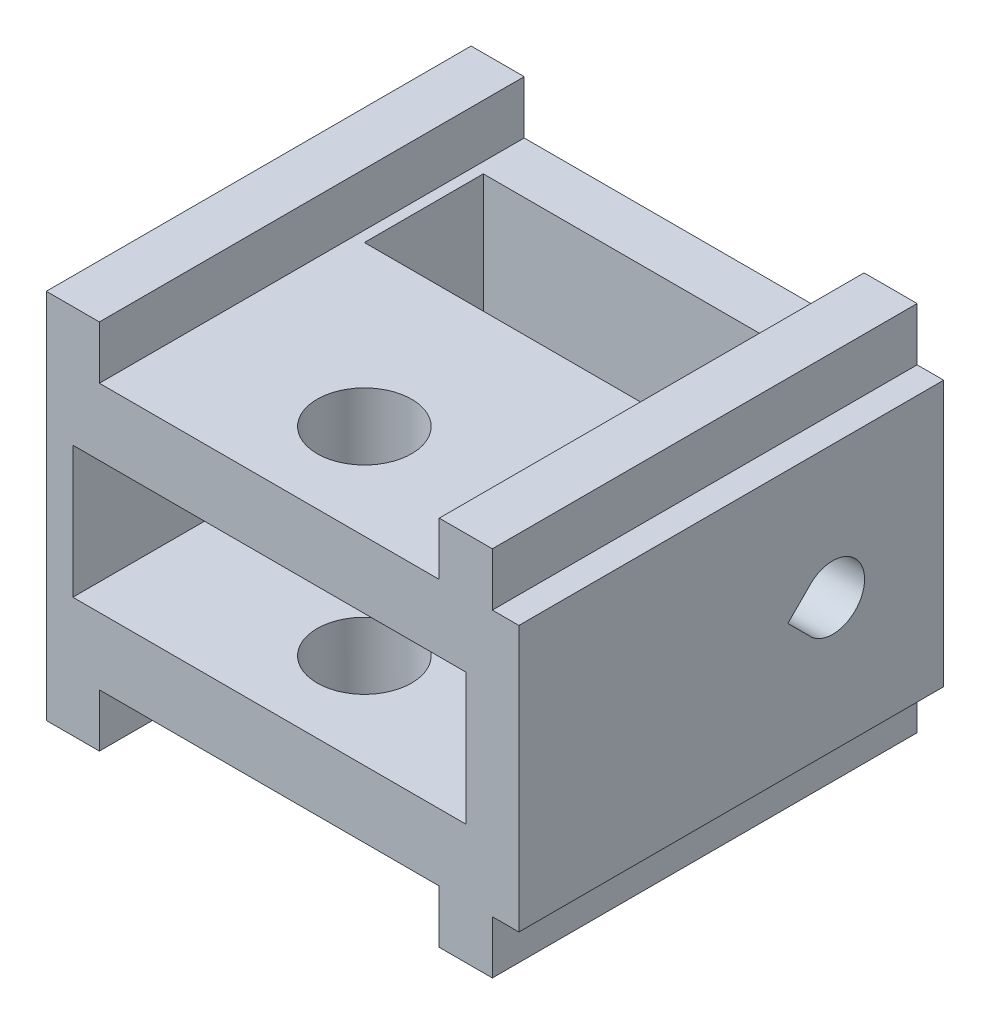
SolidWorks part; units mm, degrees
ref_plane "Front Plane" through (0, 0, 0) normal (1, 0, 0) x (0, 1, 0)
ref_plane "Top Plane" through (0, 0, 0) normal (0, 0, 1) x (0, 1, 0)
ref_plane "Right Plane" through (0, 0, 0) normal (0, 1, 0) x (-1, 0, 0)
sketch "Sketch1" plane through (0, 0, 0) normal (0, 1, 0) x (-1, 0, 0)
  line L1 (-19.5258, 0.7216) -> (22.4742, 0.7216)
  line L2 (-19.5258, 0.7216) -> (-19.5258, 40.7216)
  line L3 (-19.5258, 40.7216) -> (22.4742, 40.7216)
  line L4 (22.4742, 0.7216) -> (22.4742, 40.7216)
  dimension "D1" = 42
  dimension "D2" = 40
extrude "Boss-Extrude1" add sketch "Sketch1" along normal blind 25
sketch "Sketch2" plane through (0, 25, 0) normal (0, 1, 0) x (-1, 0, 0)
  line L0 (-19.5258, 40.7216) -> (-19.5258, 0.7216) construction
  line L1 (-13.5258, 16.7716) -> (16.4742, 16.7716)
  line L2 (-13.5258, 16.7716) -> (-13.5258, 5.5716)
  line L3 (-13.5258, 5.5716) -> (16.4742, 5.5716)
  line L4 (16.4742, 16.7716) -> (16.4742, 5.5716)
  line L5 (-19.5258, 0.7216) -> (22.4742, 0.7216) construction
  line L6 (22.4742, 0.7216) -> (22.4742, 40.7216) construction
  line L8 (-13.5258, 11.1716) -> (16.4742, 11.1716) construction
  circle A0 centre (1.4742, 31.7716) radius 4.45
  dimension "D4" = 8.9
  dimension "D5" = 15
  dimension "D6" = 21
  dimension "D7" = 11.2
  dimension "D8" = 21
  dimension "D1" = 6
  dimension "D2" = 10.45
  dimension "D3" = 30
  dimension "D9" = 31.05
  dimension "D10" = 6
extrude "Cut-Extrude1" cut sketch "Sketch2" against normal blind 25
sketch "Sketch5" plane through (0, 0, 40.7216) normal (0, 0, 1) x (1, 0, 0)
  line L1 (-19.9742, 18.7) -> (17.0258, 18.7)
  line L2 (-19.9742, 18.7) -> (-19.9742, 6.3)
  line L3 (-19.9742, 6.3) -> (17.0258, 6.3)
  line L4 (17.0258, 18.7) -> (17.0258, 6.3)
  line L8 (-22.4742, 25) -> (19.5258, 25) construction
  line L9 (-22.4742, 0) -> (19.5258, 0) construction
  line L10 (-1.4742, 25) -> (-1.4742, 0) construction
  dimension "D1" = 12.4
  dimension "D2" = 6.3
  dimension "D3" = 6.3
  dimension "D4" = 37
extrude "Cut-Extrude3" cut sketch "Sketch5" against normal up to surface (23.95 mm away) up to face at (-1.4742, 12.5, 16.7716)
sketch "Sketch7" plane through (0, 25, 0) normal (0, 1, 0) x (-1, 0, 0)
  line L0 (22.4742, 0.7216) -> (22.4742, 40.7216) construction
  line L1 (17.4742, 0.7216) -> (22.4742, 0.7216)
  line L2 (17.4742, 0.7216) -> (17.4742, 40.7216)
  line L3 (17.4742, 40.7216) -> (22.4742, 40.7216)
  line L4 (22.4742, 0.7216) -> (22.4742, 40.7216)
  line L5 (22.4742, 40.7216) -> (-19.5258, 40.7216) construction
  line L6 (-19.5258, 0.7216) -> (22.4742, 0.7216) construction
  line L7 (1.4742, 40.7216) -> (1.4742, 0.7216) construction
  line L9 (-14.5258, 40.7216) -> (-19.5258, 40.7216)
  line L10 (-19.5258, 0.7216) -> (-19.5258, 40.7216)
  line L11 (-14.5258, 0.7216) -> (-19.5258, 0.7216)
  line L12 (-14.5258, 0.7216) -> (-14.5258, 40.7216)
  dimension "D1" = 5
  dimension "D2" = 0
sketch "Sketch8" plane through (0, 0, 0) normal (0, -1, 0) x (1, 0, 0)
  line L0 (19.5258, 40.7216) -> (19.5258, 0.7216) construction
  line L1 (14.5258, 0.7216) -> (19.5258, 0.7216)
  line L2 (14.5258, 0.7216) -> (14.5258, 40.7216)
  line L3 (14.5258, 40.7216) -> (19.5258, 40.7216)
  line L4 (19.5258, 0.7216) -> (19.5258, 40.7216)
  line L5 (-22.4742, 40.7216) -> (19.5258, 40.7216) construction
  line L6 (-1.4742, 40.7216) -> (-1.4742, 0.7216) construction
  line L7 (19.5258, 0.7216) -> (-22.4742, 0.7216) construction
  line L8 (-17.4742, 40.7216) -> (-22.4742, 40.7216)
  line L9 (-22.4742, 0.7216) -> (-22.4742, 40.7216)
  line L10 (-17.4742, 0.7216) -> (-22.4742, 0.7216)
  line L11 (-17.4742, 0.7216) -> (-17.4742, 40.7216)
  line M11 (19.5258, 40.7216) -> (-22.4742, 40.7216)
  line M12 (-22.4742, 40.7216) -> (-22.4742, 0.7216)
  line M13 (-22.4742, 0.7216) -> (19.5258, 0.7216)
  dimension "D1" = 5
extrude "Boss-Extrude2" add sketch "Sketch7" along normal blind 5
extrude "Boss-Extrude3" add sketch "Sketch8" along normal blind 5 contours L11 M13 M11 M12 | L2 L3 L4 L1
sketch "Sketch10" plane through (19.5258, 0, 0) normal (1, 0, 0) x (0, 0, -1)
  line L0 (-0.7216, 30) -> (-0.7216, -5) construction
  line L1 (-0.7216, 0) -> (-40.7216, 0)
  line L2 (-0.7216, 0) -> (-0.7216, 25)
  line L3 (-0.7216, 25) -> (-40.7216, 25)
  line L4 (-40.7216, 0) -> (-40.7216, 25)
  line L5 (-40.7216, 30) -> (-40.7216, -5) construction
  line L6 (-0.7216, -5) -> (-40.7216, -5) construction
  line L7 (-40.7216, 30) -> (-0.7216, 30) construction
  dimension "D1" = 5
  dimension "D2" = 5
  dimension "D3" = 25
extrude "Boss-Extrude4" add sketch "Sketch10" along normal blind 2.5
sketch "Sketch3" plane through (19.5258, 0, 0) normal (1, 0, 0) x (0, 1, 0)
  line L0 (25, 0.7216) -> (0, 0.7216) construction
  line L1 (0, 40.7216) -> (0, 0.7216) construction
  line L2 (14.4236, 13.4738) -> (12.5, 15.3974)
  line L3 (12.5, 15.3974) -> (10.5764, 13.4738)
  arc A0 (10.5764, 13.4738) -> (14.4236, 13.4738) centre (12.5, 11.1716) ccw
  dimension "D1" = 6
  dimension "D2" = 10.45
  dimension "D3" = 12.5
extrude "Cut-Extrude2" cut sketch "Sketch3" against normal through all both and the other way through all
